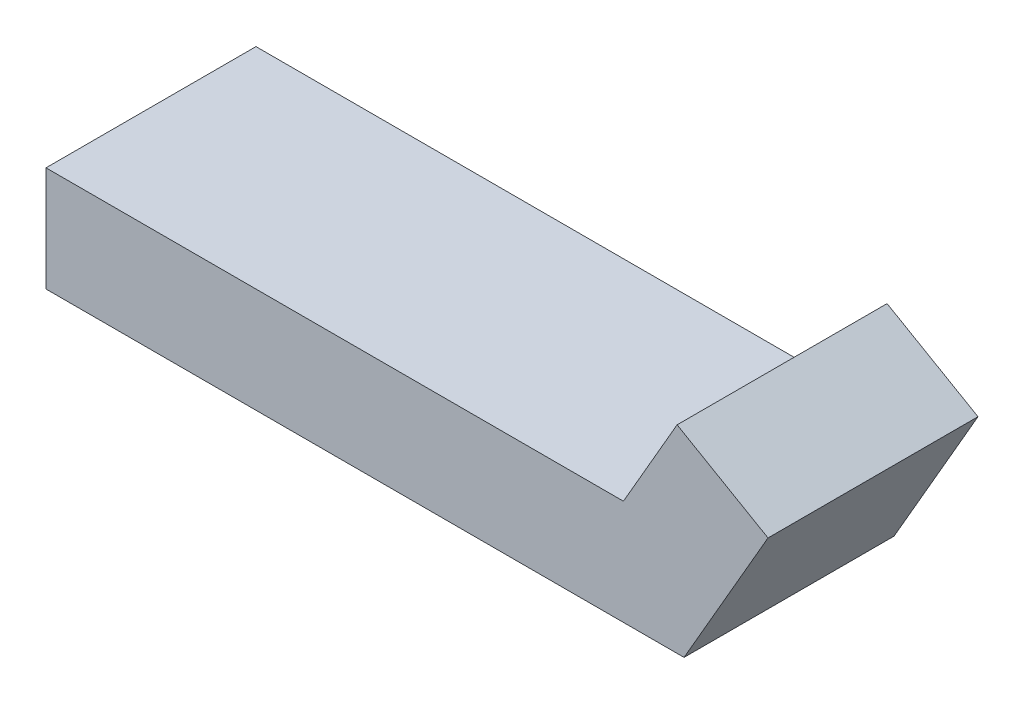
SolidWorks part; units mm, degrees
ref_plane "Front Plane" through (0, 0, 0) normal (0, 0, 1) x (1, 0, 0)
ref_plane "Top Plane" through (0, 0, 0) normal (0, 1, 0) x (1, 0, 0)
ref_plane "Right Plane" through (0, 0, 0) normal (1, 0, 0) x (0, 0, -1)
sketch "Sketch1" plane through (0, 0, 0) normal (0, 0, 1) x (1, 0, 0)
  line L0 (-21.7443, 5.8191) -> (13.1807, 5.8191)
  line L1 (13.1807, 5.8191) -> (16.4276, 11.4429)
  line L2 (16.4276, 11.4429) -> (21.9269, 8.2679)
  line L3 (21.9269, 8.2679) -> (16.8469, -0.5309)
  line L4 (16.8469, -0.5309) -> (-21.7443, -0.5309)
  line L5 (-21.7443, -0.5309) -> (-21.7443, 5.8191)
  dimension "D1" = 34.925
  dimension "D2" = 120
  dimension "D3" = 6.35
  dimension "D4" = 6.35
  dimension "D5" = 10.16
extrude "Boss-Extrude1" add sketch "Sketch1" along normal blind 12.7
